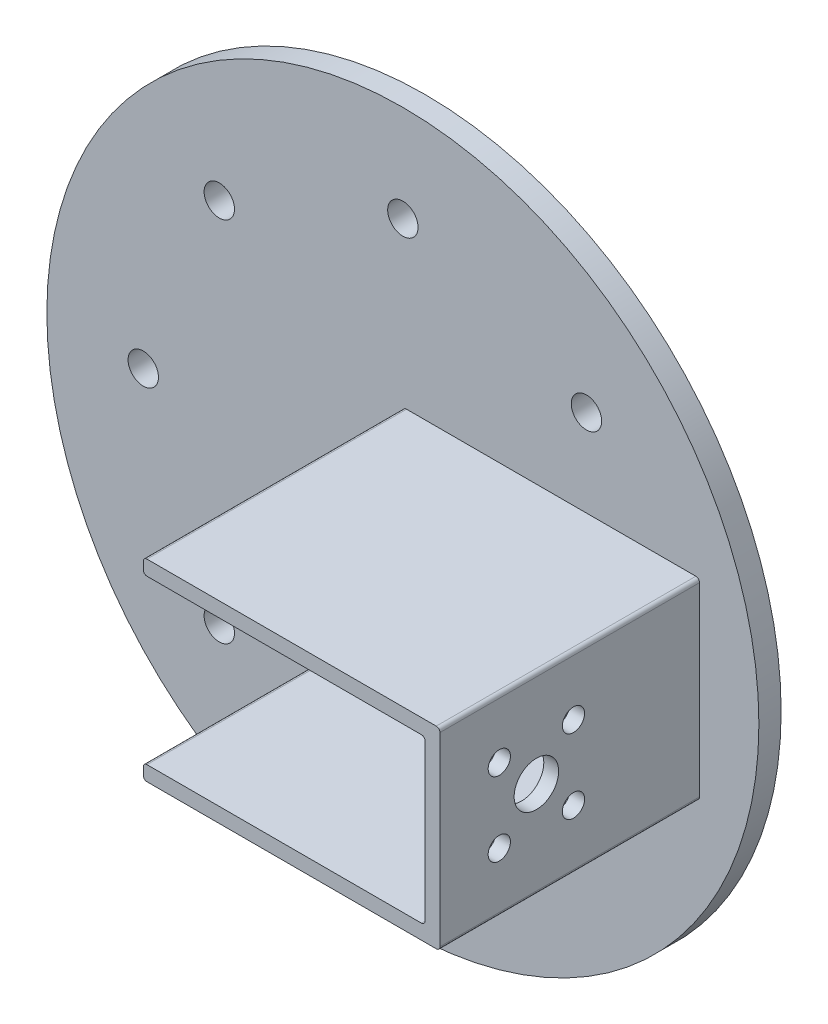
SolidWorks part; units mm, degrees
ref_plane "前视基准面" through (0, 0, 0) normal (0, 0, 1) x (1, 0, 0)
ref_plane "上视基准面" through (0, 0, 0) normal (0, 1, 0) x (1, 0, 0)
ref_plane "右视基准面" through (0, 0, 0) normal (1, 0, 0) x (0, 0, -1)
other "Configuration Table"
sketch "草图3" plane through (0, 0, 0) normal (0, 0, 1) x (1, 0, 0)
  circle A0 centre (0, 0) radius 48
  dimension "D1" = 96
extrude "凸台-拉伸2" add sketch "草图3" along normal blind 3
sketch "草图4" plane through (0, 0, 3) normal (0, 0, 1) x (1, 0, 0)
  circle A0 centre (0, 0) radius 3
  dimension "D1" = 6
extrude "切除-拉伸1" cut sketch "草图4" against normal blind 3
sketch "草图5" plane through (0, 0, 3) normal (0, 0, 1) x (1, 0, 0)
  line L0 (0, 0) -> (38, 0)
  line L1 (38, 0) -> (38, 10.5)
  line L2 (38, 0) -> (38, -10.5)
  line L3 (37.5, -11) -> (0.5, -11)
  line L4 (37.5, 11) -> (0.5, 11)
  line L5 (0, 11.5) -> (0, 12.5)
  line L6 (0.5, 13) -> (39.5, 13)
  line L7 (40, 12.5) -> (40, -12.5)
  line L8 (0, -11.5) -> (0, -12.5)
  line L9 (0.5, -13) -> (39.5, -13)
  arc A0 (0.5, -13) -> (0, -12.5) centre (0.5, -12.5) cw
  arc A1 (0, -11.5) -> (0.5, -11) centre (0.5, -11.5) cw
  arc A2 (39.5, -13) -> (40, -12.5) centre (39.5, -12.5) ccw
  arc A3 (37.5, -11) -> (38, -10.5) centre (37.5, -10.5) ccw
  arc A4 (40, 12.5) -> (39.5, 13) centre (39.5, 12.5) ccw
  arc A5 (38, 10.5) -> (37.5, 11) centre (37.5, 10.5) ccw
  arc A6 (0, 11.5) -> (0.5, 11) centre (0.5, 11.5) ccw
  arc A7 (0, 12.5) -> (0.5, 13) centre (0.5, 12.5) cw
  point P17 (40, -13)
  point P20 (38, -11)
  point P23 (40, 13)
  point P26 (38, 11)
  point P29 (0, 11)
  point P32 (0, 13)
  dimension "D7" = 0.5
  dimension "D1" = 38
  dimension "D2" = 11
  dimension "D3" = 11
  dimension "D4" = 2
  dimension "D5" = 40
  dimension "D6" = 26
extrude "凸台-拉伸3" add sketch "草图5" along normal blind 35 contours A7 L5 A6 L4 A5 L1 L2 A3 L3 A1 L8 A0 L9 A2 L7 A4 L6
sketch "草图6" plane through (40, 0, 0) normal (1, 0, 0) x (0, 0, -1)
  line L0 (-3, 0) -> (-25, 0)
  line L1 (-3, 48) -> (-3, -48) construction
  line L3 (-30, -5) -> (-20, -5)
  line L4 (-30, -5) -> (-30, 5)
  line L5 (-30, 5) -> (-20, 5)
  line L6 (-20, -5) -> (-20, 5)
  line L7 (-30, -5) -> (-20, 5) construction
  line L8 (-30, 5) -> (-20, -5) construction
  circle A0 centre (-25, 0) radius 3
  circle A1 centre (-30, 5) radius 1.5
  circle A2 centre (-20, 5) radius 1.5
  circle A3 centre (-20, -5) radius 1.5
  circle A4 centre (-30, -5) radius 1.5
  dimension "D2" = 6
  dimension "D5" = 3
  dimension "D1" = 22
  dimension "D3" = 10
  dimension "D4" = 10
  dimension "D6" = 4
extrude "切除-拉伸2" cut sketch "草图6" against normal blind 35
sketch "草图7" plane through (0, 0, 3) normal (0, 0, 1) x (1, 0, 0)
  line L0 (0, 0) -> (-35, 0)
  circle A4 centre (-35, 0) radius 1.55
  circle A5 centre (-24.7487, 24.7487) radius 1.55
  circle A6 centre (0, 35) radius 1.55
  circle A7 centre (24.7487, 24.7487) radius 1.55
  circle A8 centre (35, 0) radius 1.55
  circle A9 centre (24.7487, -24.7487) radius 1.55
  circle A10 centre (0, -35) radius 1.55
  circle A11 centre (-24.7487, -24.7487) radius 1.55
  dimension "D3" = 8
  dimension "D2" = 3.1
  dimension "D1" = 35
extrude "切除-拉伸5" cut sketch "草图7" against normal blind 35 contours A5 | A4 | A11 | A10 | A9 | A8 | A7 | A6
sketch "草图8" plane through (0, 0, 3) normal (0, 0, 1) x (1, 0, 0)
  circle A0 centre (0, 35) radius 2.05
  circle A1 centre (24.7487, 24.7487) radius 2.05
  circle A2 centre (35, 0) radius 2.05
  circle A3 centre (24.7487, -24.7487) radius 2.05
  circle A4 centre (0, -35) radius 2.05
  circle A5 centre (-24.7487, -24.7487) radius 2.05
  circle A6 centre (-35, 0) radius 2.05
  circle A7 centre (-24.7487, 24.7487) radius 2.05
  dimension "D1" = 4.1
  dimension "D2" = 8
extrude "切除-拉伸6" cut sketch "草图8" against normal blind 10
sketch "草图9" plane through (0, 0, 3) normal (0, 0, 1) x (1, 0, 0)
  line L1 (-5, -5) -> (5, -5)
  line L2 (-5, -5) -> (-5, 5)
  line L3 (-5, 5) -> (5, 5)
  line L4 (5, -5) -> (5, 5)
  line L5 (-5, -5) -> (5, 5) construction
  line L6 (-5, 5) -> (5, -5) construction
  circle A0 centre (-5, 5) radius 1.55
  circle A1 centre (5, 5) radius 1.55
  circle A2 centre (5, -5) radius 1.55
  circle A3 centre (-5, -5) radius 1.55
  point P0 (0, 0)
  dimension "D3" = 3.1
  dimension "D1" = 10
  dimension "D2" = 10
  dimension "D4" = 4
extrude "切除-拉伸7" cut sketch "草图9" against normal blind 10 contours A1 | A0 | A3 | A2
